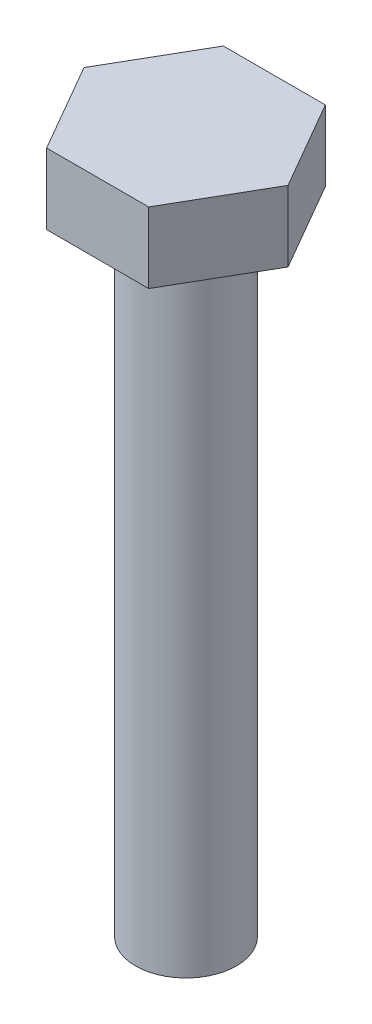
SolidWorks part; units mm, degrees
ref_plane "前视基准面" through (0, 0, 0) normal (0, 0, 1) x (1, 0, 0)
ref_plane "上视基准面" through (0, 0, 0) normal (0, 1, 0) x (1, 0, 0)
ref_plane "右视基准面" through (0, 0, 0) normal (1, 0, 0) x (0, 0, -1)
sketch "草图1" plane through (0, 0, 0) normal (0, 1, 0) x (1, 0, 0)
  circle A0 centre (0, 0) radius 2
  dimension "D1" = 4
extrude "凸台-拉伸1" add sketch "草图1" along normal blind 25
sketch "草图2" plane through (0, 25, 0) normal (0, 1, 0) x (1, 0, 0)
  line L1 (4.0415, 0) -> (2.0207, 3.5)
  line L2 (2.0207, 3.5) -> (-2.0207, 3.5)
  line L3 (-2.0207, 3.5) -> (-4.0415, 0)
  line L4 (-4.0415, 0) -> (-2.0207, -3.5)
  line L5 (-2.0207, -3.5) -> (2.0207, -3.5)
  line L6 (2.0207, -3.5) -> (4.0415, 0)
  circle A0 centre (0, 0) radius 3.5 construction
  dimension "D1" = 7
extrude "凸台-拉伸2" add sketch "草图2" along normal blind 2.8
